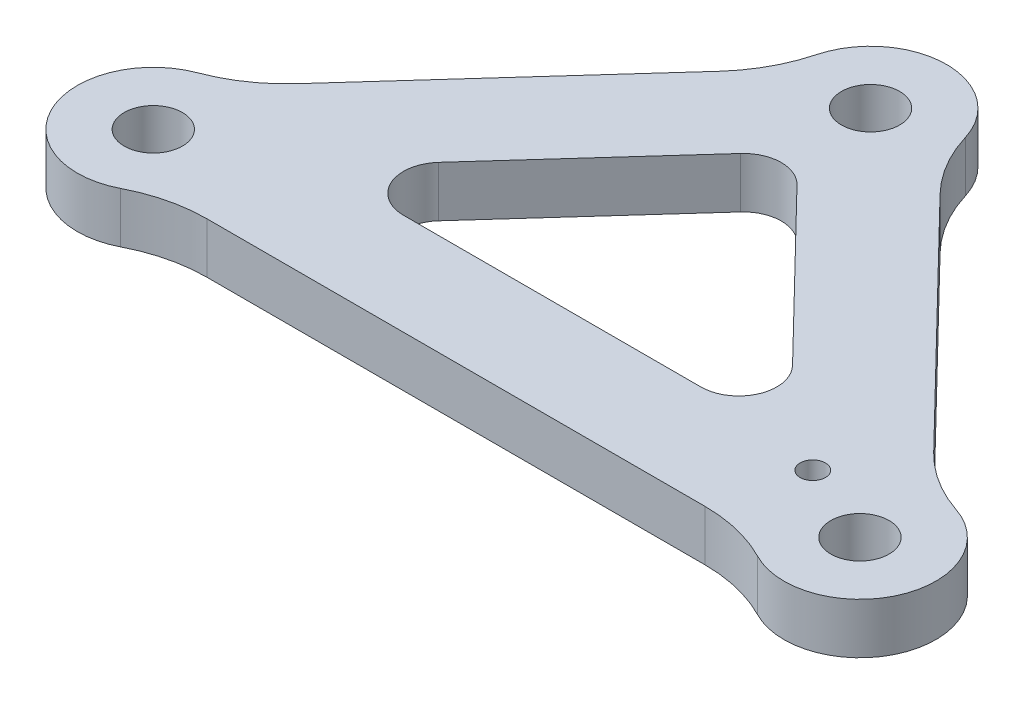
SolidWorks part; units mm, degrees
ref_plane "Спереди" through (0, 0, 0) normal (0, 0, 1) x (1, 0, 0)
ref_plane "Сверху" through (0, 0, 0) normal (0, 1, 0) x (1, 0, 0)
ref_plane "Справа" through (0, 0, 0) normal (1, 0, 0) x (0, 0, -1)
sketch "Эскиз1" plane through (0, 0, 0) normal (0, 1, 0) x (1, 0, 0)
  line L0 (0, 0) -> (27.9, 0) construction
  line L2 (0, 0) -> (13.4382, 14.8801) construction
  line L3 (25.6639, -2) -> (2.2361, -2)
  line L4 (13.4382, 14.8801) -> (27.9, 0) construction
  line L5 (10.4552, 14.5611) -> (0.0144, 3)
  line L6 (16.4308, 14.6705) -> (27.7758, 2.9974)
  line L7 (13.4917, 11.9554) -> (4.5011, 2)
  line L8 (23.1673, 2) -> (4.5011, 2)
  line L9 (13.4917, 11.9554) -> (23.1673, 2)
  line L10 (27.9, 0) -> (23.1673, 2) construction
  circle A0 centre (0, 0) radius 1.15
  circle A2 centre (27.9, 0) radius 1.15
  arc A3 (25.6639, -2) -> (27.7758, 2.9974) centre (27.9, 0) ccw
  circle A4 centre (13.4382, 14.8801) radius 1.15
  arc A5 (16.4308, 14.6705) -> (10.4552, 14.5611) centre (13.4382, 14.8801) ccw
  arc A6 (0.0144, 3) -> (2.2361, -2) centre (0, 0) ccw
  arc A7 (4.5011, 2) -> (4.5011, 2) centre (4.5011, 2) ccw
  arc A8 (23.1673, 2) -> (23.1673, 2) centre (23.1673, 2) ccw
  arc A9 (13.4917, 11.9554) -> (13.4917, 11.9554) centre (13.4917, 11.9554) ccw
  circle A10 centre (27.9, 0) radius 3.5 construction
  circle A11 centre (24.6761, 1.3624) radius 0.5
  point P16 (6.7191, 7.4401)
  dimension "D4" = 2.3
  dimension "D5" = 2.3
  dimension "D6" = 6
  dimension "D7" = 20.05
  dimension "D8" = 2.3
  dimension "D9" = 6
  dimension "D12" = 3
  dimension "D1" = 27.9
  dimension "D2" = 20.75
  dimension "D3" = 2
  dimension "D10" = 2
  dimension "D11" = 2
  dimension "D13" = 4
extrude "Бобышка-Вытянуть1" add sketch "Эскиз1" along normal blind 2
fillet "Скругление1" radius 6 6 edges at (25.6639, 1, 2) (16.4308, 1, -14.6705) (10.4552, 1, -14.5611) (0.0144, 1, -3) (2.2361, 1, 2) (27.7758, 1, -2.9974)
fillet "Скругление2" radius 1.5 3 edges at (13.4917, 1, -11.9554) (4.5011, 1, -2) (23.1673, 1, -2)
